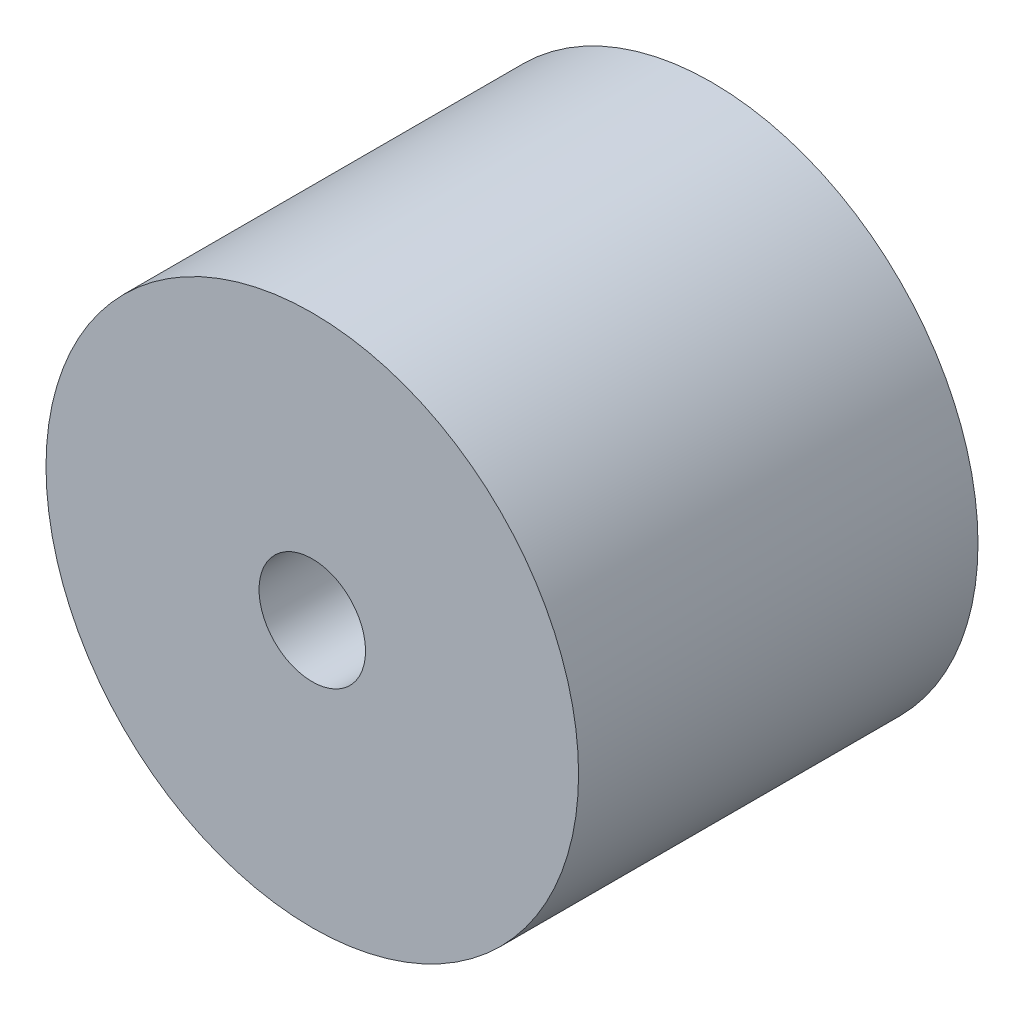
SolidWorks part; units mm, degrees
ref_plane "前视基准面" through (0, 0, 0) normal (0, 0, 1) x (1, 0, 0)
ref_plane "上视基准面" through (0, 0, 0) normal (0, 1, 0) x (1, 0, 0)
ref_plane "右视基准面" through (0, 0, 0) normal (1, 0, 0) x (0, 0, -1)
other "Configuration Table"
sketch "草图1" plane through (0, 0, 0) normal (0, 0, 1) x (1, 0, 0)
  circle A0 centre (0, 0) radius 10
  dimension "D1" = 20
extrude "凸台-拉伸1" add sketch "草图1" along normal blind 15
sketch "草图2" plane through (0, 0, 15) normal (0, 0, 1) x (1, 0, 0)
  circle A0 centre (0, 0) radius 2
  dimension "D1" = 4
extrude "切除-拉伸1" cut sketch "草图2" against normal blind 6
